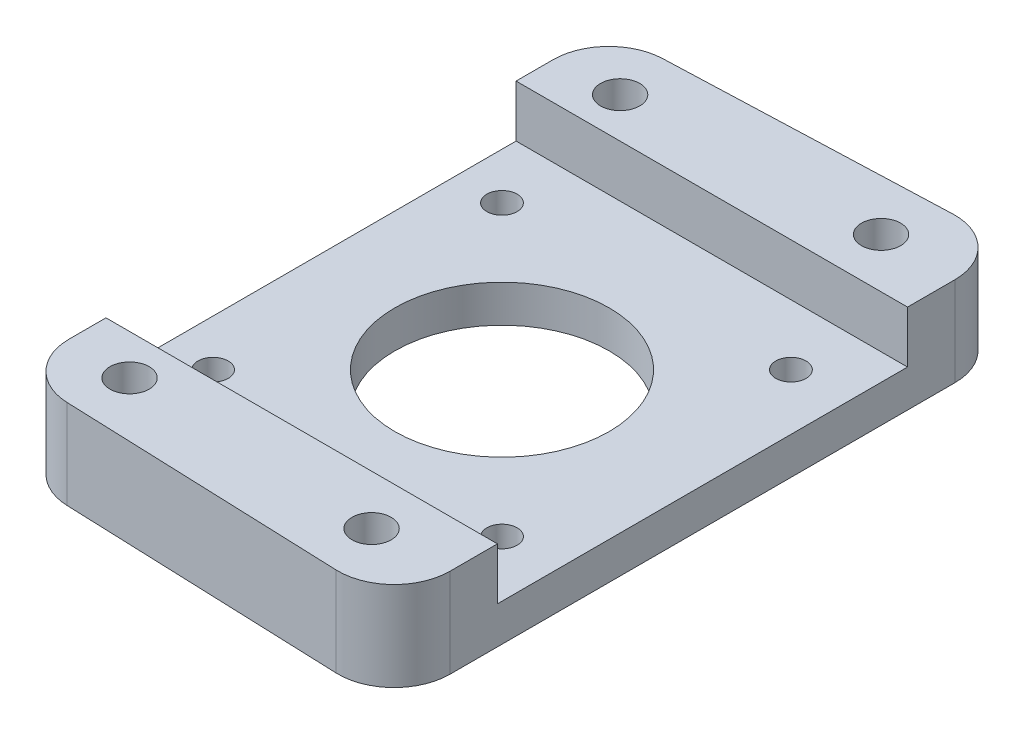
SolidWorks part; units mm, degrees
ref_plane "Front Plane" through (0, 0, 0) normal (0, 0, 1) x (1, 0, 0)
ref_plane "Top Plane" through (0, 0, 0) normal (0, 1, 0) x (1, 0, 0)
ref_plane "Right Plane" through (0, 0, 0) normal (1, 0, 0) x (0, 0, -1)
sketch "Sketch1" plane through (0, 0, 0) normal (0, 1, 0) x (1, 0, 0)
  line L1 (21.5102, -33.3133) -> (-20.4898, -31.7331)
  line L2 (21.5102, -33.3133) -> (21.5102, 33.3133)
  line L3 (21.5102, 33.3133) -> (-20.4898, 31.7331)
  line L4 (-20.4898, -31.7331) -> (-20.4898, 31.7331)
  line L5 (21.5102, -33.3133) -> (-20.4898, 31.7331) construction
  line L6 (21.5102, 33.3133) -> (-20.4898, -31.7331) construction
  line L12 (-133, 27.5) -> (65.6841, 34.9753) construction
  point P0 (0, 0)
  dimension "D1" = 42
extrude "Boss-Extrude1" add sketch "Sketch1" along normal blind 4
sketch "Sketch3" plane through (0, 4, 0) normal (0, 1, 0) x (1, 0, 0)
  circle A0 centre (0, 0) radius 11.5
  dimension "22.4" = 23
extrude "Cut-Extrude1" cut sketch "Sketch3" against normal through all
sketch "Sketch4" plane through (0, 4, 0) normal (0, 1, 0) x (1, 0, 0)
  line L0 (-15.5, 15.5) -> (15.5, 15.5) construction
  line L1 (15.5, 15.5) -> (15.5, -15.5) construction
  line L2 (15.5, -15.5) -> (-15.5, -15.5) construction
  line L3 (-15.5, -15.5) -> (-15.5, 15.5) construction
  circle A0 centre (-15.5, 15.5) radius 1.625
  circle A1 centre (15.5, 15.5) radius 1.625
  circle A2 centre (15.5, -15.5) radius 1.625
  circle A3 centre (-15.5, -15.5) radius 1.625
  point P8 (15.5, 0)
  point P9 (0, 15.5)
  dimension "D2" = 3.25
  dimension "D1" = 31
extrude "Cut-Extrude2" cut sketch "Sketch4" against normal through all
sketch "Sketch6" plane through (0, 4, 0) normal (0, -1, 0) x (1, 0, 0)
  line L0 (-20.4898, 22) -> (-20.4898, 31.7331)
  line L1 (-20.4898, -31.7331) -> (-20.4898, 31.7331) construction
  line L2 (-20.4898, 31.7331) -> (21.5102, 33.3133)
  line L3 (21.5102, 33.3133) -> (21.5102, 22)
  line L4 (21.5102, 33.3133) -> (21.5102, -33.3133) construction
  line L5 (21.5102, 22) -> (-20.4898, 22)
  dimension "D1" = 22
extrude "Boss-Extrude2" add sketch "Sketch6" against normal blind 5.575
mirror "Mirror1" about plane through (0, 0, 0) normal (0, 0, 1) of "Boss-Extrude2"
sketch "Sketch7" plane through (0, 9.575, 0) normal (0, 1, 0) x (1, 0, 0)
  circle A0 centre (13.3405, 27.3317) radius 2.1
  circle A1 centre (-13.6405, 26.3166) radius 2.1
  circle A2 centre (-13.6405, -26.3166) radius 2.1
  circle A3 centre (13.3405, -27.3317) radius 2.1
  dimension "D1" = 4.2
extrude "Cut-Extrude3" cut sketch "Sketch7" against normal blind 6
fillet "Fillet1" radius 6 4 edges at (-20.4898, 4.7875, -31.7331) (21.5102, 4.7875, -33.3133) (21.5102, 4.7875, 33.3133) (-20.4898, 4.7875, 31.7331)
